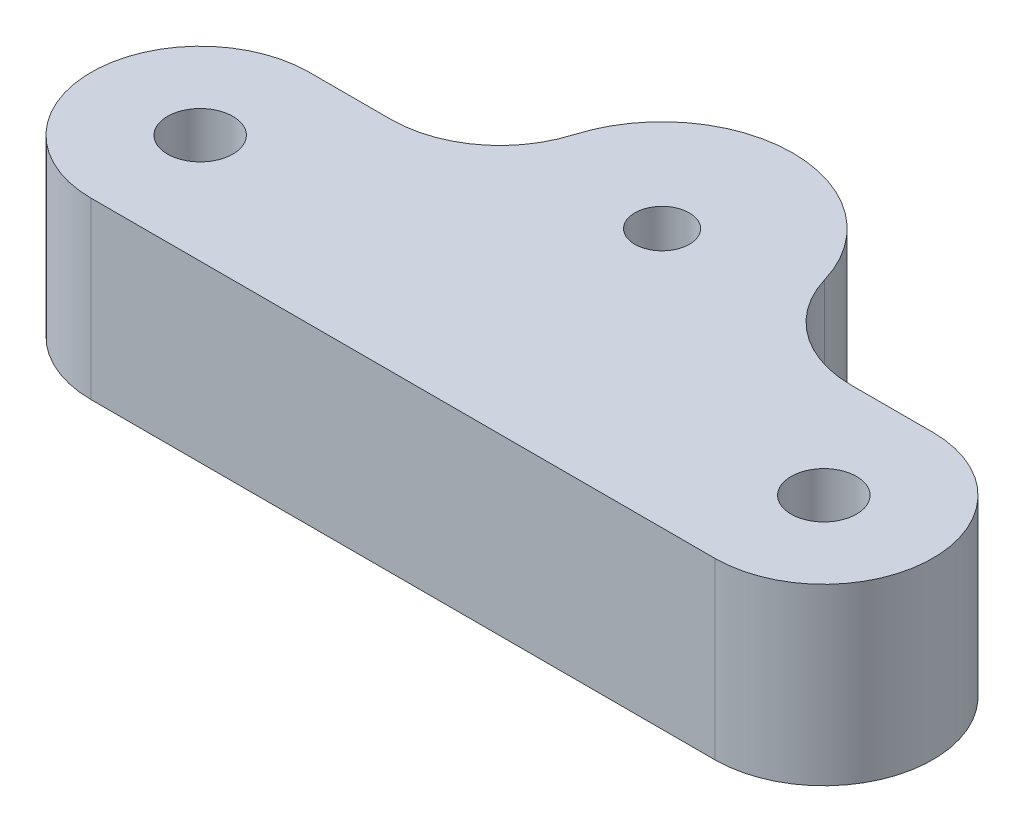
SolidWorks part; units mm, degrees
material "6061 合金"
ref_plane "前视基准面" through (0, 0, 0) normal (0, 0, 1) x (1, 0, 0)
ref_plane "上视基准面" through (0, 0, 0) normal (0, 1, 0) x (1, 0, 0)
ref_plane "右视基准面" through (0, 0, 0) normal (1, 0, 0) x (0, 0, -1)
sketch "草图1" plane through (0, 0, 0) normal (0, 1, 0) x (1, 0, 0)
  line L0 (-14.295, 0) -> (14.295, 0) construction
  line L1 (-14.295, 5) -> (14.295, 5)
  line L2 (-14.295, -5) -> (14.295, -5)
  arc A0 (-14.295, 5) -> (-14.295, -5) centre (-14.295, 0) ccw
  arc A1 (14.295, -5) -> (14.295, 5) centre (14.295, 0) ccw
  circle A2 centre (-14.295, 0) radius 1.5
  circle A3 centre (14.295, 0) radius 1.5
  point P3 (0, 0)
  dimension "D2" = 3
  dimension "D3" = 3
  dimension "D4" = 5
  dimension "D1" = 28.59
extrude "凸台-拉伸1" add sketch "草图1" along normal blind 8
sketch "草图2" plane through (0, 8, 0) normal (0, 1, 0) x (1, 0, 0)
  line L1 (-6, 6.88) -> (-6, 5)
  line L2 (14.295, 5) -> (-14.295, 5) construction
  line L3 (6, 6.88) -> (6, 5)
  line L4 (-6, 5) -> (6, 5)
  arc A0 (6, 6.88) -> (-6, 6.88) centre (0, 6.88) ccw
  dimension "D1" = 6
  dimension "D2" = 1.88
extrude "凸台-拉伸2" add sketch "草图2" against normal blind 8
sketch "草图3" plane through (0, 0, 0) normal (0, -1, 0) x (1, 0, 0)
  line L0 (-6, -5) -> (-14.295, -5) construction
  circle A0 centre (0, -6.88) radius 3.25
  arc A1 (-6, -6.88) -> (6, -6.88) centre (0, -6.88) ccw construction
  dimension "D1" = 6.5
extrude "切除-拉伸1" cut sketch "草图3" against normal blind 4
fillet "圆角1" radius 5 2 edges at (-6, 4, -5) (6, 4, -5)
hole_wizard "M3 螺纹孔1" positions "3D草图1" profile "草图4" tap size "M3" standard "GB" end condition through all
sketch3d "3D草图1"
  line L0 (0, 4, -6.88) -> (0, 0, -6.88) construction
  point P0 (0, 4, -6.88)
sketch "草图4" plane through (0, 4, -6.88) normal (1, 0, 0) x (0, 0, -1)
  line L0 (0, 0) -> (0, 4)
  line L1 (0, 4) -> (1.25, 4)
  line L2 (1.25, 4) -> (1.25, 0)
  line L5 (1.25, 0) -> (0, 0)
  line L11 (0, -6.35) -> (0, 107.95) construction
  dimension "通孔螺纹孔钻头直径" = 2.5
  dimension "通孔螺纹孔钻头深度" = 4
cosmetic thread "孔螺蚊线1" parameters "D2"=3
